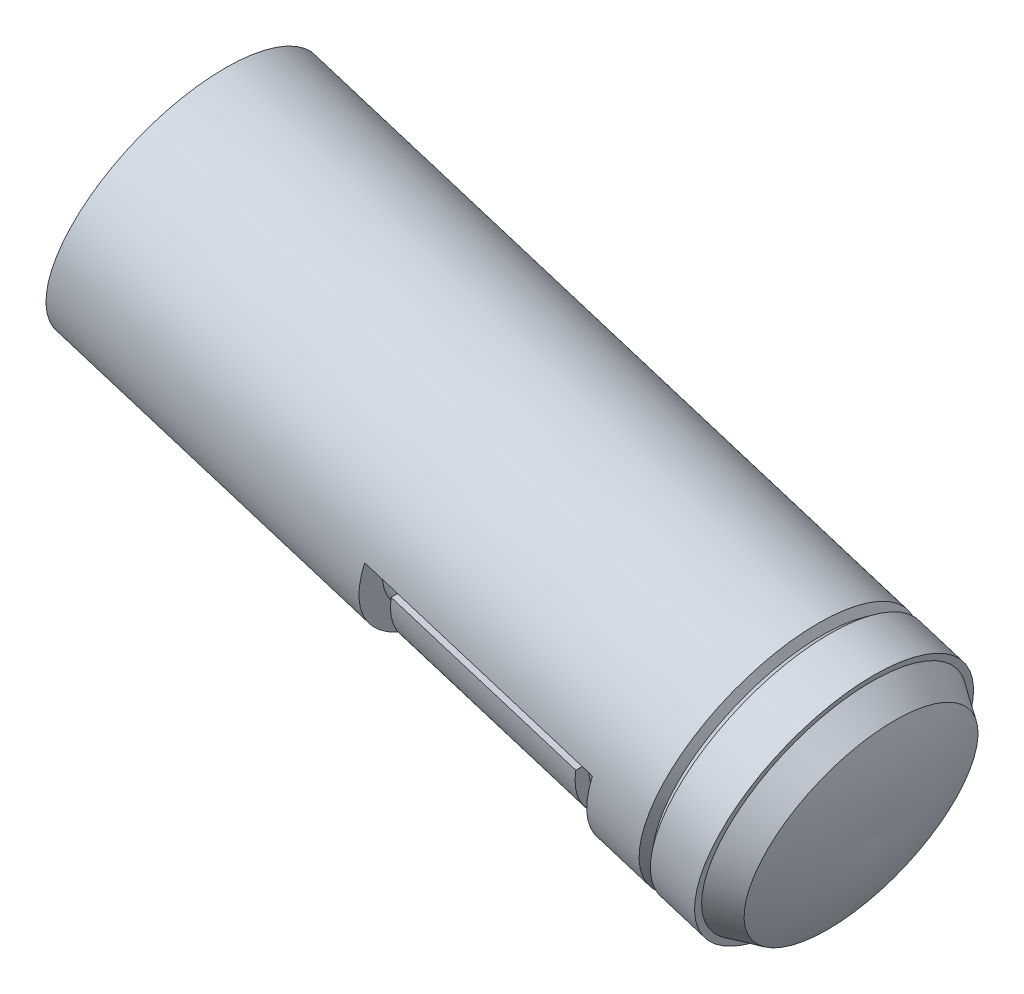
SolidWorks part; units mm, degrees
ref_plane "Front Plane" through (0, 0, 0) normal (0, 0, 1) x (1, 0, 0)
ref_plane "Top Plane" through (0, 0, 0) normal (0, 1, 0) x (1, 0, 0)
ref_plane "Right Plane" through (0, 0, 0) normal (1, 0, 0) x (0, 0, -1)
sketch "Sketch1" plane through (0, 0, 0) normal (0, 0, 1) x (1, 0, 0)
  line L0 (528.0255, 124.9874) -> (528.5085, 123.7408)
  line L1 (528.0255, 124.9874) -> (444.6576, 150.8964)
  line L2 (444.6576, 150.8964) -> (439.0774, 132.9412)
  line L3 (439.0774, 132.9412) -> (530.2457, 104.608)
  line L4 (535.5454, 121.6612) -> (535.8258, 122.5632)
  line L5 (535.8258, 122.5632) -> (529.613, 124.494)
  line L6 (528.5085, 123.7408) -> (529.613, 124.494)
  line L7 (530.2457, 104.608) -> (535.8785, 102.8575)
  line L8 (535.5454, 121.6612) -> (538.7232, 118.4834)
  arc A0 (538.7232, 118.4834) -> (535.8785, 102.8575) centre (493.8737, 118.5765) cw
  dimension "D2" = 1.5875
revolve "Revolve1" add sketch "Sketch1" angle 360 about L3
ref_plane "Plane1" through (438.7368, -136.3503, 0) normal (0.9549, -0.2968, 0) x (0, 0, -1)
sketch "Sketch3" plane through (438.7368, -136.3503, 0) normal (0.9549, -0.2968, 0) x (0, 0, -1)
  line L0 (-19.9617, 257.2602) -> (-15.6273, 257.2602)
  line L1 (15.6273, 257.2602) -> (19.9617, 257.2602)
  circle A0 centre (0, 257.2602) radius 18.8023 construction
  arc A1 (-15.6273, 257.2602) -> (15.6273, 257.2602) centre (0, 257.2602) ccw
  arc A2 (-19.9617, 257.2602) -> (19.9617, 257.2602) centre (0, 257.2602) ccw
  dimension "D1" = 3.175
extrude "Cut-Extrude1" cut sketch "Sketch3" against normal blind 33.528 contours A1 L1 A2 L0
ref_plane "Plane2" through (435.7049, -135.4081, 0) normal (-0.9549, 0.2968, 0) x (0, 0, 1)
sketch "Sketch4" plane through (435.7049, -135.4081, 0) normal (-0.9549, 0.2968, 0) x (0, 0, 1)
  line L0 (17.1714, 254.0852) -> (-17.1714, 254.0852)
  arc A0 (-17.1714, 254.0852) -> (17.1714, 254.0852) centre (0, 257.2602) ccw
  dimension "D2" = 34.925
  dimension "D1" = 3.175
extrude "Boss-Extrude1" add sketch "Sketch4" along normal offset from surface (27.178 mm away) 3.175 contours A0 L0 up to face at (480.5139, 111.0501, 0)
